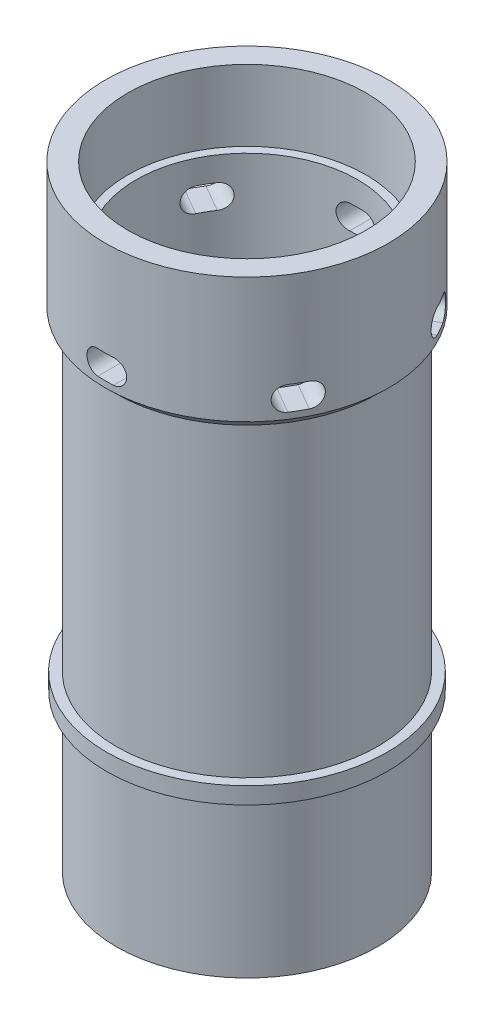
SolidWorks part; units mm, degrees
material "1060 Alloy"
ref_plane "Front Plane" through (0, 0, 0) normal (0, 0, 1) x (1, 0, 0)
ref_plane "Top Plane" through (0, 0, 0) normal (0, 1, 0) x (1, 0, 0)
ref_plane "Right Plane" through (0, 0, 0) normal (1, 0, 0) x (0, 0, -1)
sketch "Sketch1" plane through (0, 0, 0) normal (0, 1, 0) x (1, 0, 0)
  circle A0 centre (0, 0) radius 17.2085
  circle A1 centre (0, 0) radius 14.478
  dimension "D1" = 34.417
  dimension "D2" = 28.956
extrude "Boss-Extrude1" add sketch "Sketch1" against normal blind 15.24
ref_plane "Plane1" through (0, -8.636, 0) normal (0, 1, 0) x (-1, 0, 0)
sketch "Sketch2" plane through (0, -8.636, 0) normal (0, 1, 0) x (-1, 0, 0)
  circle A0 centre (0, 0) radius 15.875
  circle A1 centre (0, 0) radius 13.462
  dimension "D1" = 31.75
  dimension "D2" = 26.924
extrude "Boss-Extrude2" add sketch "Sketch2" against normal blind 66.1162
ref_plane "Plane2" through (0, -53.6702, 0) normal (0, 1, 0) x (-1, 0, 0)
sketch "Sketch3" plane through (0, -53.6702, 0) normal (0, 1, 0) x (-1, 0, 0)
  circle A0 centre (0, 0) radius 15.875
  circle A1 centre (0, 0) radius 17.0561
  dimension "D1" = 31.75
  dimension "D2" = 34.1122
extrude "Boss-Extrude3" add sketch "Sketch3" against normal blind 2.032 separate body
ref_plane "Plane3" through (0, -55.7022, 0) normal (0, 1, 0) x (-1, 0, 0)
sketch "Sketch5" plane through (0, 0, 0) normal (0, 0, 1) x (1, 0, 0)
  line L0 (14.478, 0) -> (-14.478, 0) construction
  line L1 (-0.9525, -11.5632) -> (0.9525, -11.5632)
  line L4 (-0.9525, -14.4842) -> (0.9525, -14.4842)
  arc A1 (0.9525, -14.4842) -> (0.9525, -11.5632) centre (0.9525, -13.0237) ccw
  arc A3 (-0.9525, -11.5632) -> (-0.9525, -14.4842) centre (-0.9525, -13.0237) ccw
  dimension "D1" = 1.4605
  dimension "D5" = 0.9525
  dimension "D2" = 1.905
  dimension "D3" = 11.5632
  dimension "D4" = 2.921
extrude "Cut-Extrude1" cut sketch "Sketch5" against normal mid plane 47.752
pattern_circular "CirPattern1" count 3 every 60 about axis through (0, -15.24, 0) along (0, 1, 0) of "Cut-Extrude1"
chamfer "Chamfer1" distance 1.2954 angle 45 1 edges at (0, -15.24, 15.875)
